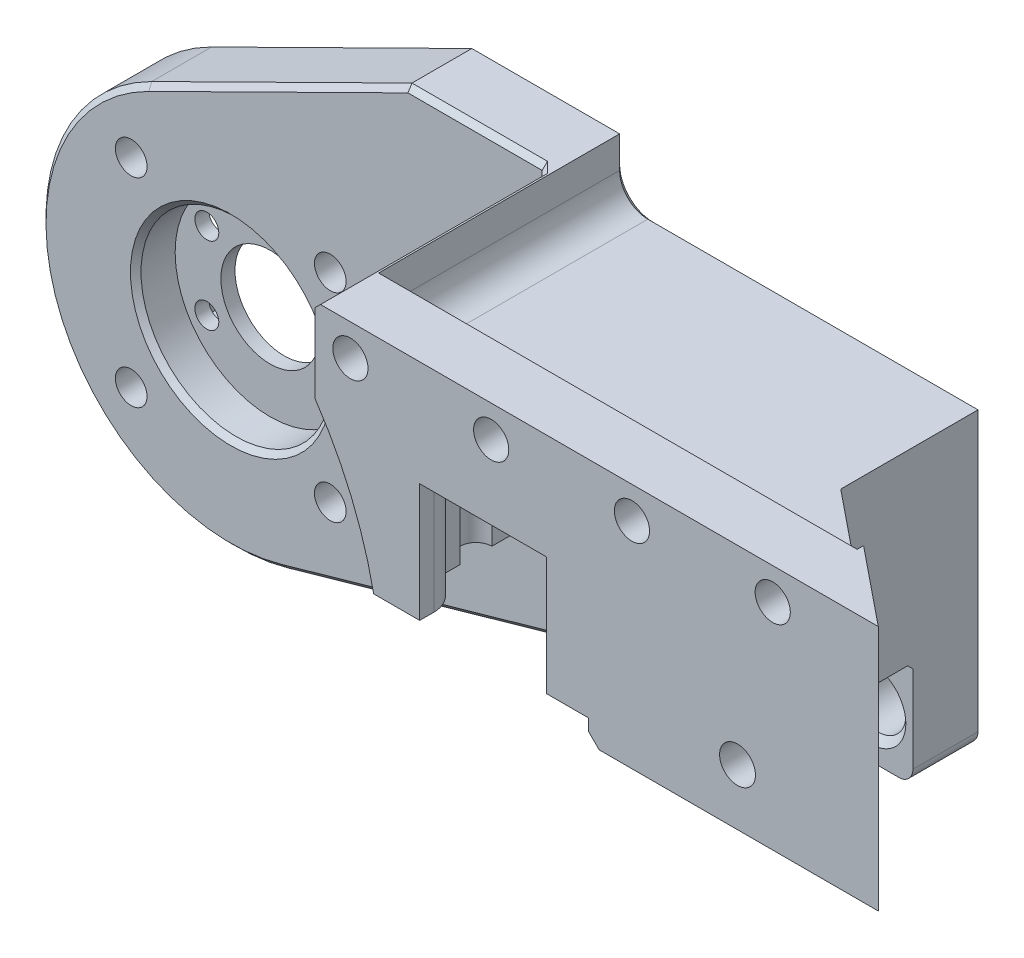
SolidWorks part; units mm, degrees
ref_plane "Front Plane" through (0, 0, 0) normal (0, 0, 1) x (1, 0, 0)
ref_plane "Top Plane" through (0, 0, 0) normal (0, 1, 0) x (1, 0, 0)
ref_plane "Right Plane" through (0, 0, 0) normal (1, 0, 0) x (0, 0, -1)
sketch "Sketch1" plane through (0, 0, 0) normal (0, 0, 1) x (1, 0, 0)
  line L0 (-135, 0) -> (135, 0)
  line L1 (135, 0) -> (135, -35)
  line L2 (135, -35) -> (-135, -35)
  line L3 (-135, -35) -> (-135, 0)
  dimension "D1" = 270
  dimension "D2" = 35
extrude "Boss-Extrude1" add sketch "Sketch1" along normal blind 10
sketch "Sketch2" plane through (0, 0, 10) normal (0, 0, 1) x (1, 0, 0)
  line L0 (135, -35) -> (135, 0) construction
  line L1 (-135, -35) -> (135, -35)
  line L2 (-135, -35) -> (-135, -9)
  line L3 (-135, -9) -> (135, -9)
  line L4 (135, -35) -> (135, -9)
  line L5 (135, 0) -> (-135, 0) construction
  dimension "D1" = 9
extrude "Boss-Extrude2" add sketch "Sketch2" along normal blind 1
sketch "Sketch3" plane through (0, 0, 10) normal (0, 0, 1) x (1, 0, 0)
  line L0 (-135, 0) -> (-135, -9) construction
  circle A0 centre (-130, -4.5) radius 2.55
  circle A1 centre (-110, -4.5) radius 2.55
  circle A2 centre (-90, -4.5) radius 2.55
  circle A3 centre (-70, -4.5) radius 2.55
  circle A4 centre (-50, -4.5) radius 2.55
  circle A5 centre (-30, -4.5) radius 2.55
  circle A6 centre (-10, -4.5) radius 2.55
  circle A7 centre (10, -4.5) radius 2.55
  circle A8 centre (30, -4.5) radius 2.55
  circle A9 centre (50, -4.5) radius 2.55
  circle A10 centre (70, -4.5) radius 2.55
  circle A11 centre (90, -4.5) radius 2.55
  point P4 (-135, -4.5)
  dimension "D1" = 5.1
  dimension "D4" = 20
  dimension "D2" = 5
  dimension "D3" = 12
extrude "Cut-Extrude1" cut sketch "Sketch3" against normal up to next
sketch "Sketch4" plane through (0, 0, 11) normal (0, 0, 1) x (1, 0, 0)
  line L0 (135, -35) -> (135, -9) construction
  line L1 (-135, 0) -> (-135, -9) construction
  circle A0 centre (123, -20.5) radius 8
  point P7 (-135, -4.5)
  dimension "D1" = 16
  dimension "D2" = 12
  dimension "D3" = 16
extrude "Cut-Extrude3" cut sketch "Sketch4" against normal up to next
sketch "Sketch5" plane through (0, 0, 11) normal (0, 0, 1) x (1, 0, 0)
  circle A0 centre (123, -20.5) radius 10
  dimension "D1" = 20
extrude "Cut-Extrude4" cut sketch "Sketch5" against normal blind 1.5
sketch "Sketch6" plane through (0, 0, 0) normal (0, 0, -1) x (-1, 0, 0)
  circle A0 centre (-123, -20.5) radius 10
  dimension "D1" = 20
extrude "Cut-Extrude5" cut sketch "Sketch6" against normal blind 1.5
sketch "Sketch8" plane through (0, 0, 0) normal (0, 0, -1) x (-1, 0, 0)
  line L0 (135, 0) -> (155, 0)
  line L1 (155, 0) -> (191.9769, -18.3018)
  line L2 (55, -35) -> (55, 0)
  line L3 (135, 0) -> (135, -35) construction
  line L4 (172.6099, -68.4689) -> (55, -35)
  line L5 (135, -35) -> (-135, -35) construction
  line L8 (-135, 0) -> (135, 0) construction
  line L9 (55, 0) -> (135, 0)
  arc A0 (191.9769, -18.3018) -> (172.6099, -68.4689) centre (180, -42.5) cw
  circle A1 centre (130, -4.5) radius 2.55 construction
  circle A2 centre (180, -42.5) radius 46 construction
  dimension "D3" = 92
  dimension "D5" = 27
  dimension "D1" = 38
  dimension "D2" = 45
  dimension "D4" = 20
  dimension "D6" = 80
extrude "Boss-Extrude3" add sketch "Sketch8" along normal blind 43
sketch "Sketch9" plane through (0, 0, 11) normal (0, 0, 1) x (1, 0, 0)
  line L0 (-135, 0) -> (-135, -35) construction
  line L1 (-135, -35) -> (135, -35) construction
  line L2 (-135, -12) -> (-135, -35)
  line L3 (-135, -35) -> (-126.1576, -35)
  arc A0 (-135, -12) -> (-126.1576, -35) centre (-180, -42.5) cw
  arc A1 (-191.9769, -18.3018) -> (-172.6099, -68.4689) centre (-180, -42.5) ccw construction
  dimension "D1" = 3
extrude "Cut-Extrude7" cut sketch "Sketch9" against normal up to surface (11 mm away) up to face at (-144.5803, -27.6015, 0)
sketch "Sketch10" plane through (0, 0, 0) normal (0, 0, 1) x (1, 0, 0)
  line L0 (-135, 0) -> (-155, 0)
  line L3 (-135, 0) -> (-135, -12) construction
  line L4 (-126.1576, -35) -> (-55, -35) construction
  line L5 (-135, 0) -> (-135, -12)
  line L6 (-126.1576, -35) -> (-55, -35)
  line L7 (-55, -35) -> (-172.6099, -68.4689) construction
  line L8 (-55, -35) -> (-172.6099, -68.4689)
  line L9 (-191.9769, -18.3018) -> (-155, 0) construction
  line L10 (-191.9769, -18.3018) -> (-155, 0)
  arc A0 (-126.1576, -35) -> (-135, -12) centre (-180, -42.5) ccw construction
  arc A1 (-126.1576, -35) -> (-135, -12) centre (-180, -42.5) ccw
  arc A2 (-191.9769, -18.3018) -> (-172.6099, -68.4689) centre (-180, -42.5) ccw construction
  arc A3 (-191.9769, -18.3018) -> (-172.6099, -68.4689) centre (-180, -42.5) ccw
extrude "Cut-Extrude8" cut sketch "Sketch10" against normal offset from surface (33 mm away) 10 up to face at (-130.4963, -26.1219, -43)
sketch "Sketch11" plane through (0, 0, -33) normal (0, 0, 1) x (1, 0, 0)
  circle A0 centre (-180, -42.5) radius 13.5
  circle A1 centre (-165.8579, -56.6421) radius 2.25
  circle A2 centre (-194.1421, -56.6421) radius 2.25
  circle A3 centre (-194.1421, -28.3579) radius 2.25
  circle A4 centre (-165.8579, -28.3579) radius 2.25
  point P14 (-180, -42.5)
  dimension "D1" = 27
  dimension "D3" = 4.5
  dimension "D2" = 20
  dimension "D4" = 4
extrude "Cut-Extrude9" cut sketch "Sketch11" against normal through all
sketch "Sketch12" plane through (0, 0, 0) normal (0, 1, 0) x (1, 0, 0)
  line L0 (-108.0837, 43) -> (-55, 0)
  line L1 (-155, 43) -> (-55, 43) construction
  line L2 (-55, 0) -> (-55, 43)
  line L3 (-55, 43) -> (-108.0837, 43)
extrude "Cut-Extrude10" cut sketch "Sketch12" against normal up to next
sketch "Sketch13" plane through (0, 0, -43) normal (0, 0, -1) x (-1, 0, 0)
  line L1 (168, -51) -> (192, -51)
  line L2 (168, -51) -> (168, -21)
  line L3 (168, -21) -> (192, -21)
  line L4 (192, -51) -> (192, -21)
  circle A1 centre (180, -42.5) radius 13.5 construction
  dimension "D1" = 24
  dimension "D2" = 30
  dimension "D3" = 12
  dimension "D4" = 8.5
extrude "Cut-Extrude11" cut sketch "Sketch13" against normal blind 2.4
sketch "Sketch14" plane through (0, 0, -40.6) normal (0, 0, -1) x (-1, 0, 0)
  circle A0 centre (180, -42.5) radius 7
  arc A1 (168, -36.3153) -> (168, -48.6847) centre (180, -42.5) ccw construction
  arc A2 (192, -36.3153) -> (168, -36.3153) centre (180, -42.5) ccw construction
  arc A3 (192, -48.6847) -> (192, -36.3153) centre (180, -42.5) ccw construction
  arc A4 (190.4881, -51) -> (192, -48.6847) centre (180, -42.5) ccw construction
  arc A5 (168, -48.6847) -> (169.5119, -51) centre (180, -42.5) ccw construction
  arc A6 (169.5119, -51) -> (190.4881, -51) centre (180, -42.5) ccw construction
  arc A7 (192, -36.3153) -> (168, -36.3153) centre (180, -42.5) ccw
  arc A8 (192, -48.6847) -> (192, -36.3153) centre (180, -42.5) ccw
  arc A9 (190.4881, -51) -> (192, -48.6847) centre (180, -42.5) ccw
  arc A10 (168, -48.6847) -> (169.5119, -51) centre (180, -42.5) ccw
  arc A11 (169.5119, -51) -> (190.4881, -51) centre (180, -42.5) ccw
  arc A12 (168, -36.3153) -> (168, -48.6847) centre (180, -42.5) ccw
  dimension "D1" = 14
extrude "Boss-Extrude4" add sketch "Sketch14" against normal blind 2
sketch "Sketch16" plane through (0, 0, -40.6) normal (0, 0, -1) x (-1, 0, 0)
  circle A0 centre (171, -37) radius 1.7
  circle A1 centre (189, -37) radius 1.7
  circle A2 centre (189, -48) radius 1.7
  circle A3 centre (171, -48) radius 1.7
  circle A4 centre (180, -42.5) radius 7 construction
  dimension "D1" = 3.4
  dimension "D2" = 18
  dimension "D3" = 11
  dimension "D4" = 9
  dimension "D5" = 5.5
extrude "Cut-Extrude12" cut sketch "Sketch16" against normal up to next
sketch "Sketch17" plane through (0, 0, -40.6) normal (0, 0, -1) x (-1, 0, 0)
  line L0 (192, -21) -> (168, -21) construction
  line L1 (168, -21) -> (192, -21)
  line L2 (168, -21) -> (168, -26)
  line L3 (168, -26) -> (192, -26)
  line L4 (192, -21) -> (192, -26)
  line L5 (168, -21) -> (168, -27.6696) construction
  line L6 (192, -27.6696) -> (192, -21) construction
  dimension "D1" = 5
extrude "Cut-Extrude13" cut sketch "Sketch17" against normal blind 2
chamfer "Chamfer1" distance 1 angle 45 4 edges at (-180, -21, -38.6) (-192, -23.5, -38.6) (-180, -26, -38.6) (-168, -23.5, -38.6)
sketch "Sketch20" plane through (0, 0, 0) normal (0, 0, 1) x (1, 0, 0)
  line L0 (-135, 0) -> (-135, -9) construction
  line L1 (135, 0) -> (-135, 0) construction
  circle A0 centre (-130, -4.5) radius 2.5
  circle A1 centre (-110, -4.5) radius 2.5
  circle A2 centre (-90, -4.5) radius 2.5
  circle A3 centre (-70, -4.5) radius 2.5
  dimension "D3" = 5
  dimension "D1" = 5
  dimension "D2" = 4.5
  dimension "D4" = 4
extrude "Cut-Extrude15" cut sketch "Sketch20" against normal up to next
sketch "Sketch18" plane through (0, 0, 11) normal (0, 0, 1) x (1, 0, 0)
  line L1 (146.3937, 8.7551) -> (-148.8584, 8.7551)
  line L2 (146.3937, 8.7551) -> (146.3937, -54.2272)
  line L3 (146.3937, -54.2272) -> (-148.8584, -54.2272)
  line L4 (-148.8584, 8.7551) -> (-148.8584, -54.2272)
extrude "Cut-Extrude14" cut sketch "Sketch18" against normal up to surface (11 mm away) up to face at (40, -17.5, 0)
sketch "Sketch21" plane through (0, 0, 0) normal (0, 0, 1) x (1, 0, 0)
  line L0 (-130, -8.5) -> (-70, -8.5)
  line L1 (-66, -4.5) -> (-66, 0)
  line L2 (-135, 0) -> (-55, 0) construction
  line L3 (-66, 0) -> (-134, 0)
  line L4 (-134, 0) -> (-134, -4.5)
  circle A0 centre (-130, -4.5) radius 4 construction
  circle A1 centre (-110, -4.5) radius 4 construction
  circle A2 centre (-90, -4.5) radius 4 construction
  circle A3 centre (-70, -4.5) radius 4 construction
  arc A4 (-134, -4.5) -> (-130, -8.5) centre (-130, -4.5) ccw
  arc A5 (-70, -8.5) -> (-66, -4.5) centre (-70, -4.5) ccw
  circle A7 centre (-130, -4.5) radius 2.5 construction
  circle A8 centre (-70, -4.5) radius 2.5 construction
  dimension "D1" = 8
  dimension "D2" = 4
extrude "Cut-Extrude16" cut sketch "Sketch21" against normal up to next from offset 8 offset against normal yes
sketch "Sketch26" plane through (0, 0, -43) normal (0, 0, -1) x (-1, 0, 0)
  line L1 (83.0837, -8.5) -> (108.0837, -8.5)
  line L2 (83.0837, -8.5) -> (83.0837, -50.1064)
  line L3 (83.0837, -50.1064) -> (108.0837, -50.1064)
  line L4 (108.0837, -8.5) -> (108.0837, -50.1064)
  dimension "D1" = 25
extrude "Boss-Extrude6" add sketch "Sketch26" against normal up to surface (10 mm away) up to face at (-141.0995, -27.9619, -33)
sketch "Sketch27" plane through (0, 0, -33) normal (0, 0, 1) x (1, 0, 0)
  line L1 (-126.1576, -35) -> (-95.7387, -35) construction
  line L2 (-83.0837, -50.1064) -> (-83.0837, -8.5) construction
  circle A0 centre (-89.0837, -43) radius 4
  dimension "D1" = 8
  dimension "D2" = 8
  dimension "D3" = 6
extrude "Cut-Extrude19" cut sketch "Sketch27" against normal offset from surface (8 mm away) 2 up to face at (-180, -38.1737, -43)
fillet "Fillet1" radius 2 1 edges at (-83.0837, -50.1064, -38)
sketch "Sketch28" plane through (0, -35, 0) normal (0, -1, 0) x (1, 0, 0)
  line L0 (-124.1576, -6) -> (-124.1576, -18)
  line L1 (-120.1576, -22) -> (-102.1576, -22)
  line L2 (-98.1576, -18) -> (-98.1576, -6)
  line L5 (-126.1576, -33) -> (-126.1576, 0) construction
  line L6 (-120.1576, -2) -> (-120.1576, 0)
  line L7 (-55, 0) -> (-126.1576, 0) construction
  line L8 (-120.1576, 0) -> (-102.1576, 0)
  line L9 (-102.1576, 0) -> (-102.1576, -2)
  arc A1 (-124.1576, -6) -> (-120.1576, -2) centre (-124.1576, -2) ccw
  arc A2 (-120.1576, -22) -> (-124.1576, -18) centre (-124.1576, -22) ccw
  arc A3 (-102.1576, -22) -> (-98.1576, -18) centre (-98.1576, -22) cw
  arc A4 (-98.1576, -6) -> (-102.1576, -2) centre (-98.1576, -2) cw
  dimension "D1" = 4
  dimension "D2" = 2
  dimension "D3" = 2
  dimension "D4" = 28
  dimension "D5" = 22
extrude "Cut-Extrude20" cut sketch "Sketch28" against normal blind 20
sketch "Sketch29" plane through (0, -35, 0) normal (0, -1, 0) x (1, 0, 0)
  line L0 (-98.1576, -18) -> (-98.1576, -6) construction
  line L1 (-129.9919, 2.4499) -> (-96.1576, 2.4499)
  line L2 (-129.9919, 2.4499) -> (-129.9919, -24)
  line L3 (-129.9919, -24) -> (-96.1576, -24)
  line L4 (-96.1576, 2.4499) -> (-96.1576, -24)
  line L5 (-120.1576, -22) -> (-102.1576, -22) construction
  dimension "D1" = 2
  dimension "D2" = 2
extrude "Cut-Extrude21" cut sketch "Sketch29" against normal blind 3.175
sketch "Sketch30" plane through (0, -31.825, 0) normal (0, -1, 0) x (1, 0, 0)
  line L0 (-124.1576, -18) -> (-124.1576, -6) construction
  line L3 (-102.1576, -22) -> (-120.1576, -22) construction
  line L4 (-98.1576, -6) -> (-98.1576, -18) construction
  line L5 (-120.1576, 0) -> (-126.6962, 0) construction
  circle A0 centre (-123.6576, -2.5) radius 1.9
  circle A1 centre (-123.6576, -21.5) radius 1.9
  circle A2 centre (-98.6576, -21.5) radius 1.9
  circle A3 centre (-98.6576, -2.5) radius 1.9
  dimension "D1" = 3.8
  dimension "D2" = 0.5
  dimension "D4" = 0.5
  dimension "D5" = 0.5
  dimension "D3" = 2.5
extrude "Cut-Extrude22" cut sketch "Sketch30" against normal blind 15
sketch "Sketch31" plane through (0, -31.825, 0) normal (0, -1, 0) x (1, 0, 0)
  line L0 (-124.1576, -18) -> (-124.1576, -6) construction
  circle A0 centre (-124.1576, -12) radius 2.25
  dimension "D1" = 4.5
extrude "Cut-Extrude23" cut sketch "Sketch31" against normal up to surface (16.825 mm away) up to face at (-111.1576, -15, -9.6)
sketch "Sketch32" plane through (0, 0, 0) normal (0, 0, 1) x (1, 0, 0)
  circle A0 centre (-75, -27) radius 2.55
  dimension "D1" = 5.1
extrude "Cut-Extrude24" cut sketch "Sketch32" against normal up to next
sketch "Sketch34" plane through (0, 0, -43) normal (0, 0, -1) x (-1, 0, 0)
  line L0 (83.0837, -8.5) -> (130, -8.5) construction
  line L1 (83.0837, -8.5) -> (95.7387, -8.5)
  line L2 (83.0837, -8.5) -> (83.0837, -35)
  line L3 (83.0837, -35) -> (95.7387, -35)
  line L4 (95.7387, -8.5) -> (95.7387, -35)
  line L5 (55, -35) -> (95.7387, -35) construction
  line L6 (83.0837, -8.5) -> (83.0837, -48.1064) construction
extrude "Boss-Extrude7" add sketch "Sketch34" against normal up to surface (10 mm away)
chamfer "Chamfer2" distance 2.25 angle 45 4 edges at (-163.6079, -56.6421, -43) (-191.8921, -56.6421, -43) (-196.3921, -28.3579, -43) (-163.6079, -28.3579, -43)
chamfer "Chamfer3" distance 1 angle 45 1 edges at (-85.0837, -43, -33)
chamfer "Chamfer4" distance 0.75 angle 45 19 edges at (-140.3468, -59.2876, -33) (-205.1882, -52.2239, -33) (-104.6207, -35, -33) (-129.2585, -22.9924, -33) (-135, -6, -33) (-135, 0, -16.5) (-145, 0, -33) (-173.4885, -9.1509, -33) (-166.5, -42.5, -33) (-96.5837, -50.1064, -43) (-134, -2.25, -43) (-83.6695, -49.5206, -43) (-132.8284, -7.3284, -43) (-83.0837, -28.3032, -43) (-106.5419, -8.5, -43) (-140.3468, -59.2876, -43) (-205.1882, -52.2239, -43) (-144.5, 0, -43) (-173.4885, -9.1509, -43)
chamfer "Chamfer6" distance 1.5 angle 45 2 edges at (-111.1576, -35, -24) (-96.1576, -35, -12)
equation "\"D4@Sketch16\"=\"D2@Sketch16\"/2"
equation "\"D5@Sketch16\"=\"D3@Sketch16\"/2"
equation "\"D4@Sketch30\"=\"D5@Sketch30\""
equation "\"D2@Sketch30\"=\"D5@Sketch30\""
equation "\"D3@Sketch30\"=2+\"D2@Sketch30\""
